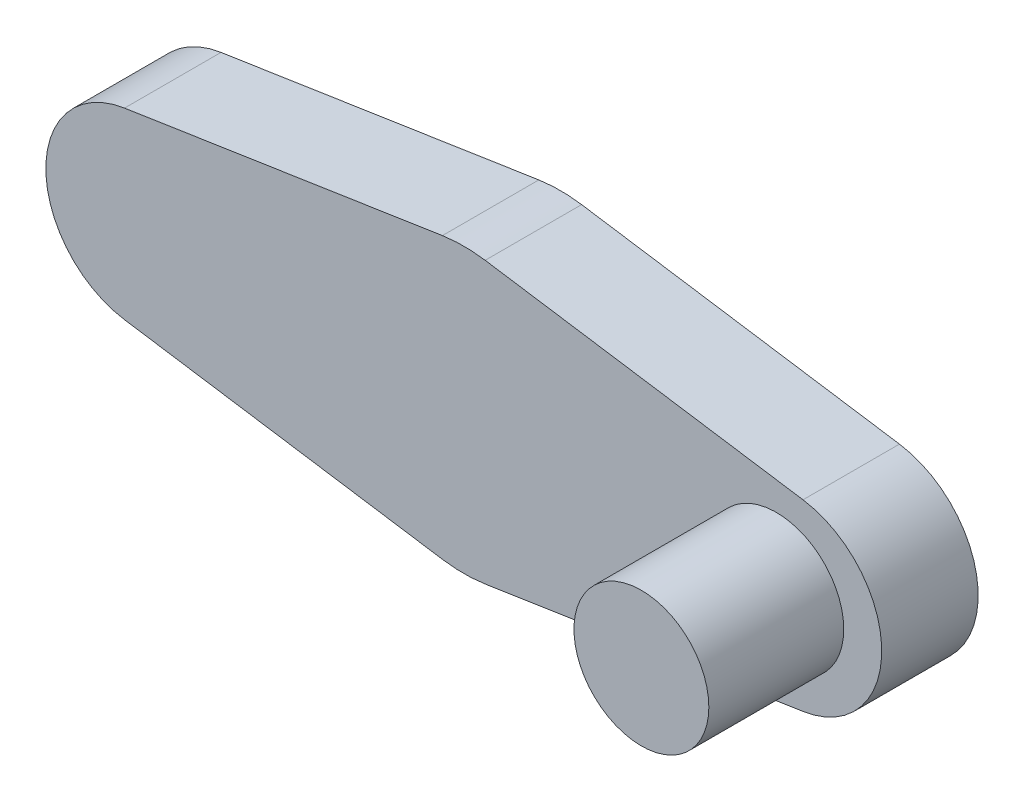
SolidWorks part; units mm, degrees
ref_plane "Front Plane" through (0, 0, 0) normal (0, 0, 1) x (1, 0, 0)
ref_plane "Top Plane" through (0, 0, 0) normal (0, 1, 0) x (1, 0, 0)
ref_plane "Right Plane" through (0, 0, 0) normal (1, 0, 0) x (0, 0, -1)
sketch "Sketch1" plane through (0, 0, 0) normal (0, 0, 1) x (1, 0, 0)
  line L0 (20.636, 1.8052) -> (5.6736, 4.0877)
  line L1 (5.6747, -4.0875) -> (20.6365, -1.8011)
  line L2 (20.5403, 1.1775) -> (5.5778, 3.46)
  line L3 (5.5787, -3.4598) -> (20.5406, -1.1733)
  line L4 (20.5403, 1.1775) -> (5.5778, 3.46)
  line L5 (5.5787, -3.4598) -> (20.5406, -1.1733)
  line L6 (6.0584, -6.5984) -> (21.0202, -4.3119)
  line L7 (21.0191, 4.3162) -> (6.0566, 6.5987)
  line L8 (5.05, 6.675) -> (5.05, -6.675) construction
  line L9 (-10.9191, 4.3162) -> (4.0434, 6.5987)
  line L10 (4.0416, -6.5984) -> (-10.9202, -4.3119)
  line L11 (4.5213, -3.4598) -> (-10.4406, -1.1733)
  line L12 (-10.4403, 1.1775) -> (4.5222, 3.46)
  line L13 (4.4253, -4.0875) -> (-10.5365, -1.8011)
  line L14 (-10.536, 1.8052) -> (4.4264, 4.0877)
  arc A0 (5.6736, 4.0877) -> (4.4264, 4.0877) centre (5.05, 0) ccw
  arc A1 (20.6365, -1.8011) -> (20.636, 1.8052) centre (20.3609, 0.0021) ccw
  arc A2 (5.5778, 3.46) -> (5.5787, -3.4598) centre (5.05, 0) ccw
  arc A3 (20.5406, -1.1733) -> (20.5403, 1.1775) centre (20.3609, 0.0021) ccw
  arc A4 (5.5778, 3.46) -> (4.5222, 3.46) centre (5.05, 0) ccw
  arc A5 (20.5406, -1.1733) -> (20.5403, 1.1775) centre (20.3609, 0.0021) ccw
  arc A6 (21.0202, -4.3119) -> (21.0191, 4.3162) centre (20.3609, 0.0021) ccw
  arc A7 (6.0566, 6.5987) -> (4.0434, 6.5987) centre (5.05, 0) ccw
  arc A8 (4.0416, -6.5984) -> (6.0584, -6.5984) centre (5.05, 0) ccw
  arc A9 (6.0566, 6.5987) -> (6.0584, -6.5984) centre (5.05, 0) ccw construction
  arc A10 (4.4253, -4.0875) -> (5.6747, -4.0875) centre (5.05, 0) ccw
  arc A11 (5.6736, 4.0877) -> (5.6747, -4.0875) centre (5.05, 0) ccw construction
  arc A12 (4.5213, -3.4598) -> (5.5787, -3.4598) centre (5.05, 0) ccw
  arc A13 (5.5778, 3.46) -> (5.5787, -3.4598) centre (5.05, 0) ccw construction
  arc A14 (-10.9202, -4.3119) -> (-10.9191, 4.3162) centre (-10.2609, 0.0021) cw
  arc A15 (-10.4406, -1.1733) -> (-10.4403, 1.1775) centre (-10.2609, 0.0021) cw
  arc A16 (-10.5365, -1.8011) -> (-10.536, 1.8052) centre (-10.2609, 0.0021) cw
  dimension "D1" = 0
  dimension "D2" = 0.635
  dimension "D3" = 2.54
extrude "Boss-Extrude1" add sketch "Sketch1" along normal blind 2 contours L7 A7 L6 A6 A1 L1 A0 L0
sketch "Sketch2" plane through (0, 0, 2) normal (0, 0, 1) x (1, 0, 0)
  line L0 (6.0584, -6.5984) -> (21.0202, -4.3119) construction
  line L1 (6.0584, -6.5984) -> (21.0202, -4.3119)
  line L4 (21.0191, 4.3162) -> (6.0566, 6.5987)
  line L5 (6.0584, -6.5984) -> (21.0202, -4.3119)
  line L6 (21.0191, 4.3162) -> (6.0566, 6.5987)
  line L7 (6.0584, -6.5984) -> (21.0202, -4.3119)
  line L10 (-10.9202, -4.3119) -> (4.0416, -6.5984)
  line L11 (-10.9202, -4.3119) -> (4.0416, -6.5984)
  line L12 (4.0434, 6.5987) -> (-10.9191, 4.3162)
  line L13 (4.0434, 6.5987) -> (-10.9191, 4.3162)
  arc A2 (6.0566, 6.5987) -> (4.0434, 6.5987) centre (5.05, 0) ccw
  arc A3 (21.0202, -4.3119) -> (21.0191, 4.3162) centre (20.3609, 0.0021) ccw
  arc A4 (6.0566, 6.5987) -> (4.0434, 6.5987) centre (5.05, 0) ccw
  arc A5 (21.0202, -4.3119) -> (21.0191, 4.3162) centre (20.3609, 0.0021) ccw
  arc A8 (-10.9191, 4.3162) -> (-10.9202, -4.3119) centre (-10.2609, 0.0021) ccw
  arc A9 (-10.9191, 4.3162) -> (-10.9202, -4.3119) centre (-10.2609, 0.0021) ccw
  arc A10 (4.0416, -6.5984) -> (6.0584, -6.5984) centre (5.05, 0) ccw
  arc A11 (4.0416, -6.5984) -> (6.0584, -6.5984) centre (5.05, 0) ccw
  arc M5 (20.636, 1.8052) -> (20.6365, -1.8011) centre (20.3609, 0.0021) cw
  line M6 (20.6365, -1.8011) -> (5.6747, -4.0875)
  arc M7 (4.4264, 4.0877) -> (5.6736, 4.0877) centre (5.05, 0) cw
  line M8 (5.6736, 4.0877) -> (20.636, 1.8052)
  line M9 (21.0191, 4.3162) -> (6.0566, 6.5987)
  arc M10 (6.0566, 6.5987) -> (4.0434, 6.5987) centre (5.05, 0) ccw
  line M11 (6.0584, -6.5984) -> (21.0202, -4.3119)
  arc M12 (21.0202, -4.3119) -> (21.0191, 4.3162) centre (20.3609, 0.0021) ccw
  dimension "D1" = 0
extrude "Boss-Extrude2" add sketch "Sketch2" along normal blind 2.54 contours M5 M8 M7 M6 | M12 M9 M10 M11 M8 M5 M6 M7
ref_plane "Plane2" through (0, 0, 2.27) normal (0, 0, 1) x (1, 0, 0)
sketch "Sketch3" plane through (0, 0, 4.54) normal (0, 0, 1) x (1, 0, 0)
  circle A0 centre (19.7613, 0) radius 3.175
  dimension "D1" = 6.35
extrude "Boss-Extrude3" add sketch "Sketch3" along normal blind 6.35
